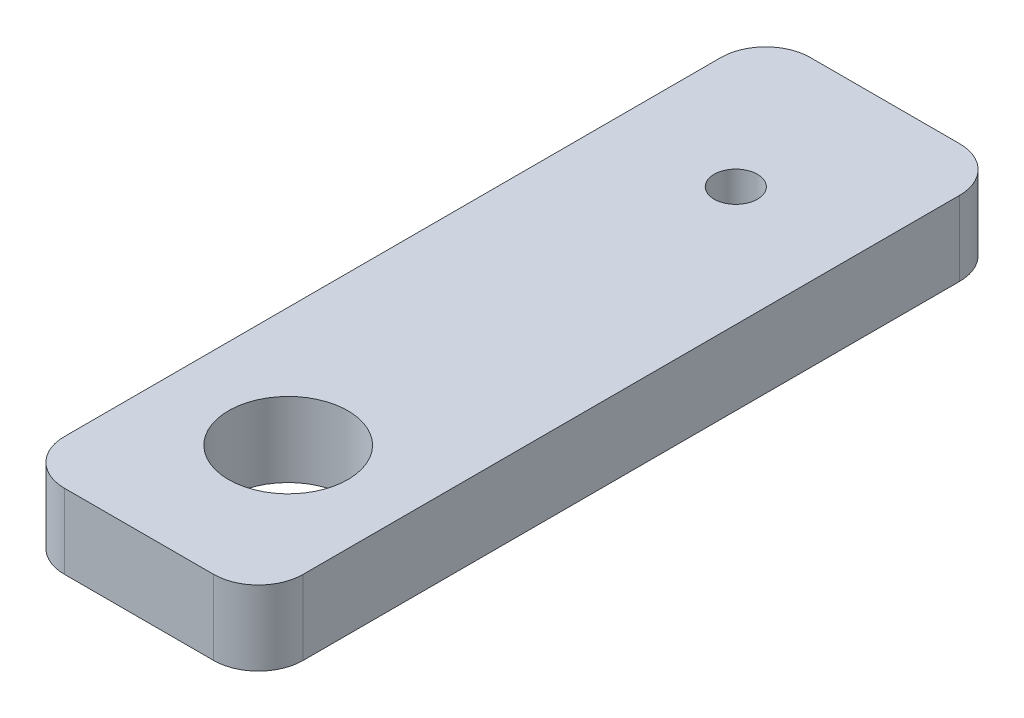
SolidWorks part; units mm, degrees
ref_plane "Front Plane" through (0, 0, 0) normal (0, 0, 1) x (1, 0, 0)
ref_plane "Top Plane" through (0, 0, 0) normal (0, 1, 0) x (1, 0, 0)
ref_plane "Right Plane" through (0, 0, 0) normal (1, 0, 0) x (0, 0, -1)
sketch "Sketch1" plane through (0, 0, 0) normal (0, 1, 0) x (1, 0, 0)
  line L5 (0, 0) -> (16, 0)
  line L6 (0, 0) -> (0, 50)
  line L7 (0, 50) -> (16, 50)
  line L8 (16, 0) -> (16, 50)
  circle A0 centre (8, 40) radius 1.45
  circle A1 centre (8, 10) radius 4
  dimension "D3" = 2.9
  dimension "D6" = 8
  dimension "D1" = 50
  dimension "D2" = 16
  dimension "D4" = 8
  dimension "D5" = 10
  dimension "D7" = 8
  dimension "D8" = 10
extrude "Boss-Extrude1" add sketch "Sketch1" along normal blind 5
fillet "Fillet1" radius 3 4 edges at (16, 2.5, -50) (0, 2.5, -50) (16, 2.5, 0) (0, 2.5, 0)
